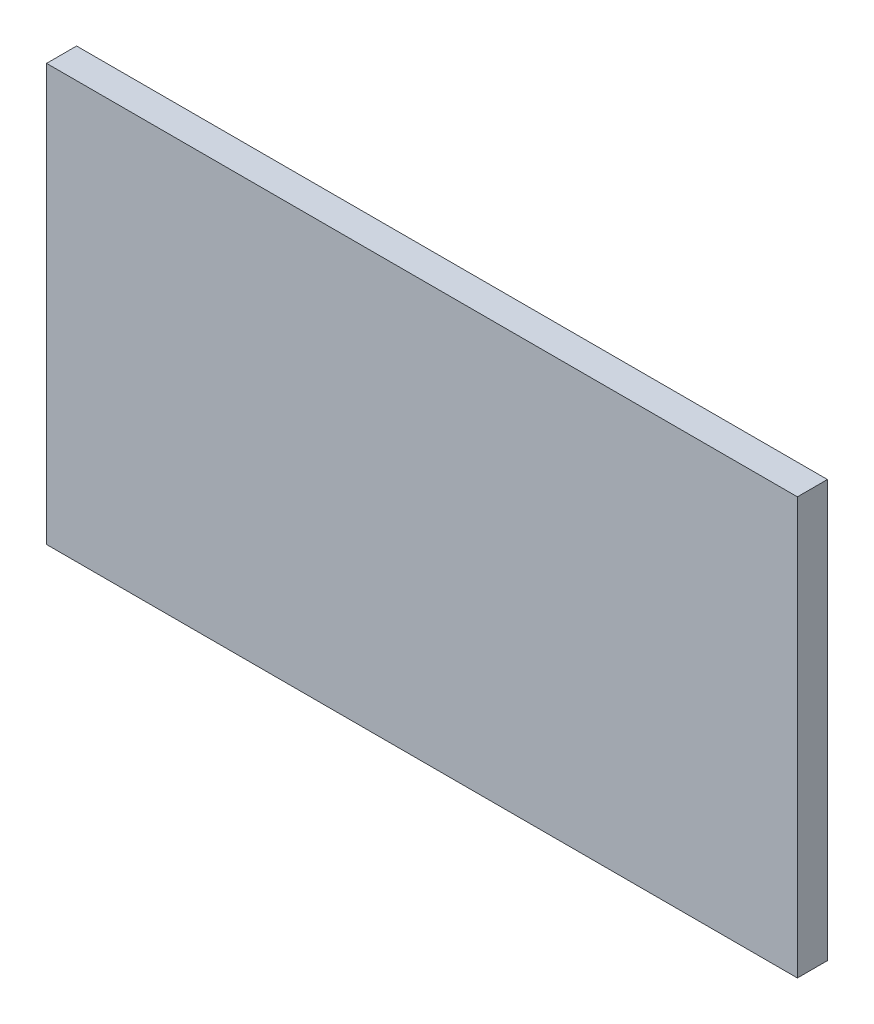
SolidWorks part; units mm, degrees
material "Plain Carbon Steel"
ref_plane "Front Plane" through (0, 0, 0) normal (0, 0, 1) x (1, 0, 0)
ref_plane "Top Plane" through (0, 0, 0) normal (0, 1, 0) x (1, 0, 0)
ref_plane "Right Plane" through (0, 0, 0) normal (1, 0, 0) x (0, 0, -1)
sketch "Sketch1" plane through (0, 0, 0) normal (0, 0, 1) x (1, 0, 0)
  line L0 (250, 0) -> (-250, 0) construction
  line L1 (-500, 5) -> (500, 5)
  line L2 (-500, 5) -> (-500, -550)
  line L3 (-500, -550) -> (500, -550)
  line L4 (500, 5) -> (500, -550)
  line L5 (500, -56) -> (500, -94) construction
  line L6 (-500, -94) -> (-500, -56) construction
  line L7 (19, -550) -> (-19, -550) construction
  dimension "D1" = 5
extrude "Boss-Extrude1" add sketch "Sketch1" along normal blind 40 contours L2 L3 L4 L1
